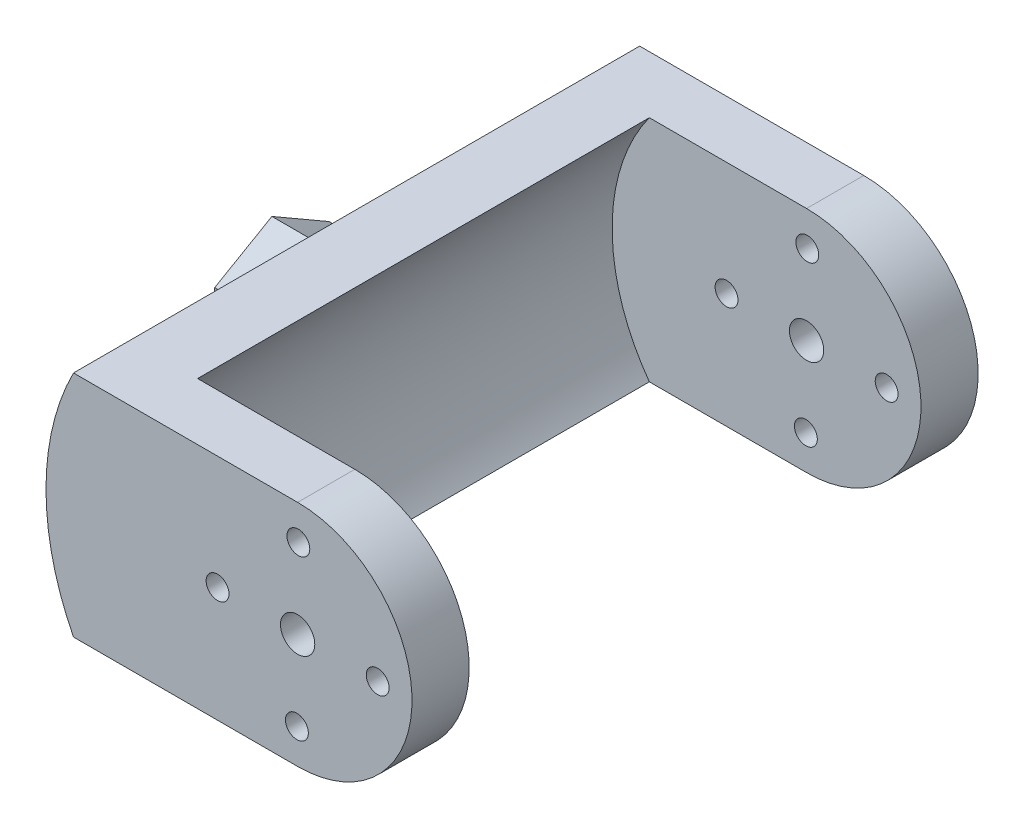
SolidWorks part; units mm, degrees
ref_plane "Plan de face" through (0, 0, 0) normal (0, 0, 1) x (1, 0, 0)
ref_plane "Plan de dessus" through (0, 0, 0) normal (0, 1, 0) x (1, 0, 0)
ref_plane "Plan de droite" through (0, 0, 0) normal (1, 0, 0) x (0, 0, -1)
sketch "Esquisse1" plane through (0, 0, 0) normal (0, 0, 1) x (1, 0, 0)
  line L0 (-13.5846, -30.0471) -> (-13.5846, -25.5471)
  line L1 (-13.8346, -25.2971) -> (-16.3346, -25.2971)
  line L2 (-16.5846, -25.0471) -> (-16.5846, 6.4529)
  line L3 (-16.3346, 6.7029) -> (-13.8346, 6.7029)
  line L4 (-13.5846, 6.9529) -> (-13.5846, 11.4529)
  line L5 (-13.3346, 11.7029) -> (-8.5846, 11.7029)
  line L6 (-8.5846, 11.7029) -> (-8.5846, 6.7029)
  line L7 (-8.5846, 6.7029) -> (-7.4918, 6.7029)
  line L8 (-7.4918, 6.7029) -> (-4.0345, 6.7029)
  line L9 (-4.0345, -25.2971) -> (-7.4918, -25.2971)
  line L10 (-7.4918, -25.2971) -> (-8.5846, -25.2971)
  line L11 (-8.5846, -25.2971) -> (-8.5846, -30.2971)
  line L12 (-8.5846, -30.2971) -> (-13.3346, -30.2971)
  line L13 (-13.3346, -30.2971) -> (-13.5846, -30.2971)
  line L14 (-13.5846, -30.2971) -> (-13.5846, -30.0471)
  line L15 (-13.5846, -25.5471) -> (-13.5846, -25.2971)
  line L16 (-13.5846, -25.2971) -> (-13.8346, -25.2971)
  line L17 (-16.3346, -25.2971) -> (-16.5846, -25.2971)
  line L18 (-16.5846, -25.2971) -> (-16.5846, -25.0471)
  line L19 (-16.3346, 6.7029) -> (-16.5846, 6.7029)
  line L20 (-16.5846, 6.7029) -> (-16.5846, 6.4529)
  line L21 (-13.5846, 6.9529) -> (-13.5846, 6.7029)
  line L22 (-13.5846, 6.7029) -> (-13.8346, 6.7029)
  line L23 (-13.5846, 11.4529) -> (-13.5846, 11.7029)
  line L24 (-13.5846, 11.7029) -> (-13.3346, 11.7029)
  arc A0 (3.4488, 4.7029) -> (-4.0345, 6.7029) centre (-4.0345, -8.2971) ccw
  arc A1 (3.4488, 4.7029) -> (18.4154, 0.7029) centre (18.4154, 30.7029) ccw
  arc A2 (18.4154, -19.2971) -> (18.4154, 0.7029) centre (18.4154, -9.2971) ccw
  arc A3 (18.4154, -19.2971) -> (3.4488, -23.2971) centre (18.4154, -49.2971) ccw
  arc A4 (-4.0345, -25.2971) -> (3.4488, -23.2971) centre (-4.0345, -10.2971) ccw
  circle A5 centre (18.4779, -2.2971) radius 1
  circle A6 centre (25.4154, -9.3596) radius 1
  circle A7 centre (18.4154, -9.2971) radius 1.5
  circle A8 centre (11.4154, -9.2347) radius 1
  circle A9 centre (18.3529, -16.2971) radius 1
extrude "Boss.-Extru.1" add sketch "Esquisse1" along normal blind 5
sketch "Esquisse2" plane through (0, 0, 0) normal (0, 0, -1) x (-1, 0, 0)
  line L0 (-18.4154, -9.2971) -> (7.3764, -9.2971) construction
  line L2 (1.5846, -19.2971) -> (1.5846, -26.2971) construction
  line L3 (4.0345, 6.7029) -> (8.5846, 6.7029) construction
  line L4 (1.5846, -19.2971) -> (1.5846, -25.2971)
  line L5 (-26.8332, -33.657) -> (-26.1987, -19.2971)
  line L6 (21.5846, -33.657) -> (-26.8332, -33.657)
  line L7 (21.5846, 7.7029) -> (1.5846, 7.7029)
  line L8 (21.5846, -26.2971) -> (21.5846, -33.657)
  line L9 (1.5846, 6.7029) -> (1.5846, 7.7029)
  line L10 (-26.1987, -19.2971) -> (1.5846, -19.2971)
  line L11 (1.5846, -25.2971) -> (1.5846, -26.2971)
  line L12 (-26.1987, 0.7029) -> (1.5846, 0.7029)
  line L13 (21.5846, -26.2971) -> (1.5846, -26.2971)
  line L15 (21.5846, 7.7029) -> (21.5846, 15.0627)
  line L16 (21.5846, 15.0627) -> (-26.8332, 15.0627)
  line L17 (-26.8332, 15.0627) -> (-26.1987, 0.7029)
  line L18 (1.5846, 0.7029) -> (1.5846, 7.7029) construction
  line L19 (1.5846, 0.7029) -> (1.5846, 6.7029)
  arc A1 (-18.4154, 0.7029) -> (-18.4154, -19.2971) centre (-18.4154, -9.2971) ccw construction
extrude "Enlèv. mat.-Extru.1" cut sketch "Esquisse2" against normal blind 5
sketch "Esquisse3" plane through (0, 0, 0) normal (0, 0, -1) x (-1, 0, 0)
  line L0 (8.5846, 7.7029) -> (13.5846, 7.7029) construction
  line L1 (21.5846, -26.2971) -> (1.5846, -26.2971)
  line L2 (21.5846, -26.2971) -> (21.5846, 7.7029)
  line L3 (21.5846, 7.7029) -> (1.5846, 7.7029)
  line L4 (1.5846, -26.2971) -> (1.5846, 7.7029)
  line L5 (13.5846, -26.2971) -> (8.5846, -26.2971) construction
  dimension "D1" = 0
  dimension "D2" = 20
  dimension "D3" = 0
extrude "Boss.-Extru.2" add sketch "Esquisse3" against normal blind 5
sketch "Esquisse4" plane through (0, 0, 0) normal (0, 0, -1) x (-1, 0, 0)
  line L1 (21.5846, -26.2971) -> (1.5846, -26.2971) construction
  line L2 (1.5846, -26.2971) -> (1.5846, -19.2971) construction
  line L4 (28.8831, -28.9494) -> (19.0846, -28.9494)
  line L5 (28.8831, -28.9494) -> (28.8831, 10.9087)
  line L6 (28.8831, 10.9087) -> (19.0846, 10.9087)
  line L7 (19.0846, -28.9494) -> (19.0846, 10.9087)
  circle A0 centre (9.0846, -22.7971) radius 1.5
  circle A1 centre (9.0846, 4.2029) radius 1.5
  dimension "D1" = 7.5
  dimension "D4" = 3
  dimension "D5" = 3
  dimension "D6" = 10
  dimension "D2" = 27
  dimension "D3" = 3.5
extrude "Enlèv. mat.-Extru.2" cut sketch "Esquisse4" against normal blind 5
sketch "Esquisse5" plane through (0, 0, 0) normal (0, 0, -1) x (-1, 0, 0)
  line L1 (1.5846, -26.2971) -> (-0.9154, -26.2971)
  line L2 (1.5846, -26.2971) -> (1.5846, 7.7029)
  line L3 (1.5846, 7.7029) -> (-0.9154, 7.7029)
  line L4 (-0.9154, -26.2971) -> (-0.9154, 7.7029)
  circle A0 centre (9.0846, -22.7971) radius 1.5 construction
  dimension "D1" = 10
extrude "Boss.-Extru.3" add sketch "Esquisse5" against normal up to vertex (5 mm away)
sketch "Esquisse6" plane through (0, 0, 0) normal (0, 0, -1) x (-1, 0, 0)
  line L0 (19.0846, -26.2971) -> (-0.9154, -26.2971) construction
  line L1 (-0.9154, 7.7029) -> (19.0846, 7.7029) construction
  line L2 (12.3246, -25.1248) -> (5.8446, -25.1248)
  line L4 (12.3246, -28.7971) -> (12.3246, -25.1248)
  line L6 (5.8446, -28.7971) -> (5.8446, -25.1248)
  line L7 (12.3246, 6.7577) -> (5.8446, 6.7577)
  line L8 (5.8446, 6.7577) -> (5.8446, 10.2029)
  line L9 (12.3246, 6.7577) -> (12.3246, 10.2029)
  circle A0 centre (9.0846, -28.7971) radius 1.6
  circle A1 centre (9.0846, 10.2029) radius 1.6
  arc A2 (5.8446, -28.7971) -> (12.3246, -28.7971) centre (9.0846, -28.7971) ccw
  arc A3 (12.3246, 10.2029) -> (5.8446, 10.2029) centre (9.0846, 10.2029) ccw
  circle A5 centre (9.0846, -22.7971) radius 1.5 construction
  dimension "D1" = 3.2
  dimension "D2" = 3.2
  dimension "D3" = 2.5
  dimension "D4" = 2.5
  dimension "D5" = 0
  dimension "D6" = 6.48
  dimension "D7" = 6.48
extrude "Boss.-Extru.4" add sketch "Esquisse6" against normal up to vertex (5 mm away)
ref_plane "Plan1" through (0, 0, -39.5) normal (0, 0, -1) x (-1, 0, 0)
sketch "Esquisse7" plane through (0, 0, 5) normal (0, 0, 1) x (1, 0, 0)
  line L1 (-27.2891, -36.2076) -> (1.4154, -36.2076)
  line L2 (-27.2891, -36.2076) -> (-27.2891, 16.7522)
  line L3 (-27.2891, 16.7522) -> (1.4154, 16.7522)
  line L4 (1.4154, -36.2076) -> (1.4154, 16.7522)
extrude "Enlèv. mat.-Extru.3" cut sketch "Esquisse7" against normal blind 10
sketch "Esquisse8" plane through (0, 0, -39.5) normal (0, 0, -1) x (-1, 0, 0)
  line L3 (-18.4154, -19.2971) -> (-1.4154, -19.2971)
  line L4 (-1.4154, -19.2971) -> (-1.4154, 0.7029)
  line L5 (-1.4154, 0.7029) -> (-18.4154, 0.7029)
  line L6 (-18.4154, -19.2971) -> (-1.4154, -19.2971)
  line L7 (-1.4154, -19.2971) -> (-1.4154, 0.7029)
  line L8 (-1.4154, 0.7029) -> (-18.4154, 0.7029)
  circle A1 centre (-11.4154, -9.2347) radius 1
  circle A2 centre (-11.4154, -9.2347) radius 1
  circle A3 centre (-18.3529, -16.2971) radius 1
  circle A4 centre (-18.3529, -16.2971) radius 1
  circle A5 centre (-18.4154, -9.2971) radius 1.5
  circle A6 centre (-18.4154, -9.2971) radius 1.5
  circle A7 centre (-18.4779, -2.2971) radius 1
  circle A8 centre (-18.4779, -2.2971) radius 1
  circle A9 centre (-25.4154, -9.3596) radius 1
  circle A10 centre (-25.4154, -9.3596) radius 1
  arc A11 (-18.4154, 0.7029) -> (-18.4154, -19.2971) centre (-18.4154, -9.2971) ccw
  arc A12 (-18.4154, 0.7029) -> (-18.4154, -19.2971) centre (-18.4154, -9.2971) ccw
  dimension "D1" = 0
  dimension "D2" = 0
  dimension "D3" = 0
  dimension "D4" = 0
  dimension "D5" = 0
  dimension "D6" = 0
extrude "Boss.-Extru.5" add sketch "Esquisse8" along normal blind 5 separate body
sketch "Esquisse9" plane through (0, 0, 5) normal (0, 0, 1) x (1, 0, 0)
  line L1 (4.6677, -19.2971) -> (-1.1805, -19.2971)
  line L3 (4.6677, 0.7029) -> (-1.1805, 0.7029)
  line L5 (18.4154, 0.7029) -> (1.4154, 0.7029) construction
  arc A0 (4.6677, 0.7029) -> (4.6677, -19.2971) centre (18.4154, -9.2971) ccw
  arc A1 (-1.1805, 0.7029) -> (-1.1805, -19.2971) centre (18.4154, -9.2971) ccw
  dimension "D1" = 44
extrude "Boss.-Extru.6" add sketch "Esquisse9" against normal up to vertex (49.5 mm away)
ref_plane "Plan2" through (-3.5846, 0, 0) normal (1, 0, 0) x (0, 0, -1)
sketch "Esquisse10" plane through (-3.5846, 0, 0) normal (1, 0, 0) x (0, 0, -1)
  line L0 (-5, 0.7029) -> (-5, -19.2971) construction
  line L1 (24.75, -12.1839) -> (24.75, -6.4104)
  line L2 (24.75, -6.4104) -> (19.75, -3.5236)
  line L3 (19.75, -3.5236) -> (14.75, -6.4104)
  line L4 (14.75, -6.4104) -> (14.75, -12.1839)
  line L5 (14.75, -12.1839) -> (19.75, -15.0706)
  line L6 (19.75, -15.0706) -> (24.75, -12.1839)
  line L7 (44.5, -19.2971) -> (-5, -19.2971) construction
  circle A0 centre (19.75, -9.2971) radius 5 construction
  point P11 (-5, -9.2971)
  point P14 (19.75, -19.2971)
  dimension "D1" = 10
extrude "Boss.-Extru.7" add sketch "Esquisse10" against normal blind 5 and the other way blind 1
